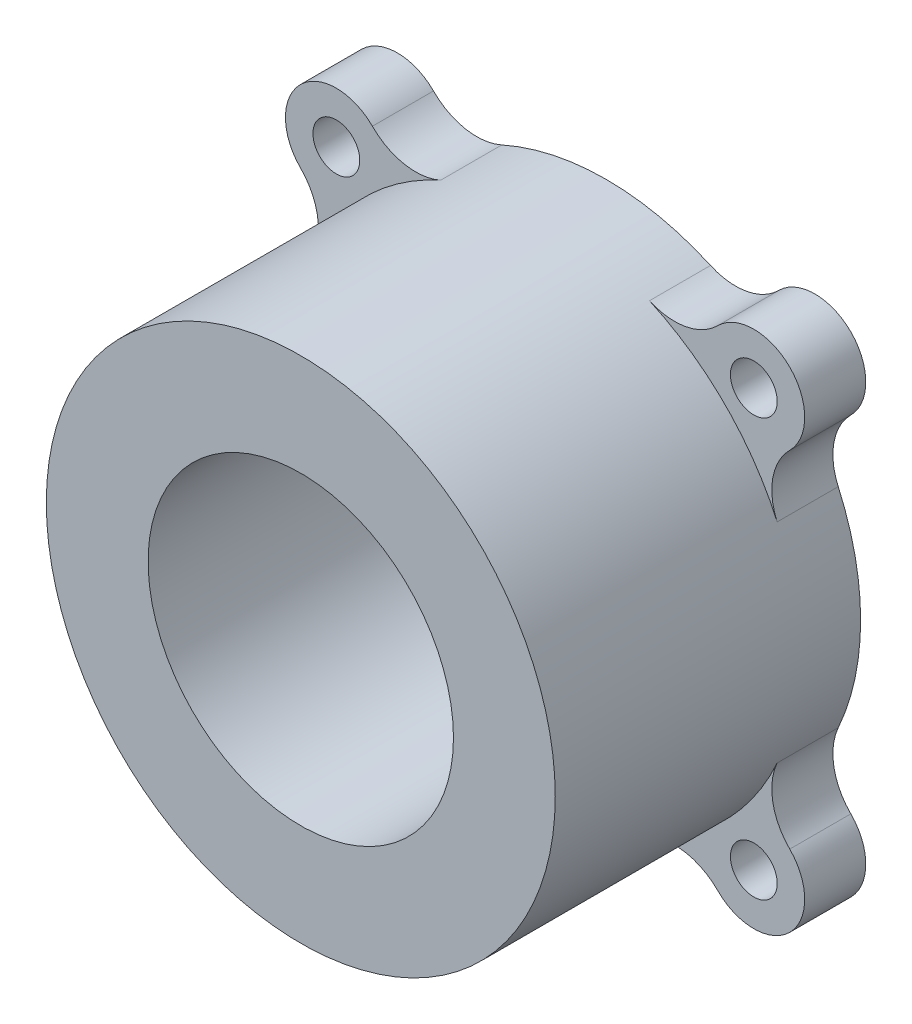
SolidWorks part; units mm, degrees
ref_plane "Płaszczyzna przednia" through (0, 0, 0) normal (0, 0, 1) x (1, 0, 0)
ref_plane "Płaszczyzna górna" through (0, 0, 0) normal (0, 1, 0) x (1, 0, 0)
ref_plane "Płaszczyzna prawa" through (0, 0, 0) normal (1, 0, 0) x (0, 0, -1)
sketch "Sketch1" plane through (0, 0, 0) normal (0, 0, 1) x (1, 0, 0)
  circle A0 centre (0, 0) radius 15
  circle A1 centre (0, 0) radius 25
  dimension "D1" = 30
  dimension "D2" = 10
extrude "Boss-Extrude1" add sketch "Sketch1" along normal blind 30
sketch "Sketch2" plane through (0, 0, 0) normal (0, 0, -1) x (-1, 0, 0)
  line L0 (0, 0) -> (17.6777, 17.6777) construction
  line L1 (20.5061, 20.5061) -> (17.6777, 17.6777) construction
  circle A0 centre (0, 0) radius 25 construction
  circle A1 centre (20.5061, 20.5061) radius 5
  circle A2 centre (20.5061, 20.5061) radius 2.3
  circle A3 centre (20.5061, -20.5061) radius 2.3
  circle A4 centre (20.5061, -20.5061) radius 5
  circle A5 centre (-20.5061, -20.5061) radius 2.3
  circle A6 centre (-20.5061, -20.5061) radius 5
  circle A7 centre (-20.5061, 20.5061) radius 2.3
  circle A8 centre (-20.5061, 20.5061) radius 5
  point P20 (0, 0)
  dimension "D1" = 10
  dimension "D3" = 4.6
  dimension "D2" = 4
  dimension "D4" = 4
extrude "Boss-Extrude2" add sketch "Sketch2" against normal blind 6
fillet "Fillet1" radius 6 8 edges at (15.6014, -19.5345, 3) (19.5345, -15.6014, 3) (-19.5345, -15.6014, 3) (-15.6014, -19.5345, 3) (-15.6014, 19.5345, 3) (-19.5345, 15.6014, 3) (19.5345, 15.6014, 3) (15.6014, 19.5345, 3)
